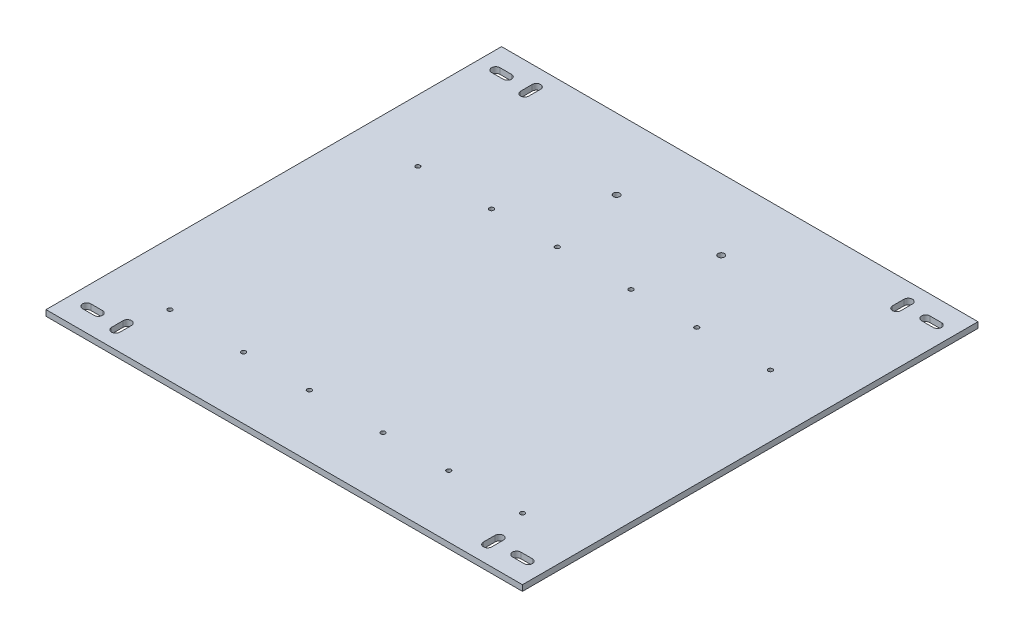
SolidWorks part; units mm, degrees
ref_plane "Front Plane" through (0, 0, 0) normal (0, 0, 1) x (1, 0, 0)
ref_plane "Top Plane" through (0, 0, 0) normal (0, 1, 0) x (1, 0, 0)
ref_plane "Right Plane" through (0, 0, 0) normal (1, 0, 0) x (0, 0, -1)
sketch "Sketch1" plane through (0, 0, 0) normal (0, 1, 0) x (1, 0, 0)
  line L1 (-205, -196) -> (205, -196)
  line L2 (-205, -196) -> (-205, 196)
  line L3 (-205, 196) -> (205, 196)
  line L4 (205, -196) -> (205, 196)
  line L5 (-205, -196) -> (205, 196) construction
  line L6 (-205, 196) -> (205, -196) construction
  point P0 (0, 0)
  dimension "D1" = 410
  dimension "D2" = 392
extrude "Boss-Extrude1" add sketch "Sketch1" along normal blind 5
sketch "Sketch2" plane through (0, 5, 0) normal (0, 1, 0) x (1, 0, 0)
  line L0 (-190, -176) -> (-180, -176) construction
  line L1 (-190, -172.4) -> (-180, -172.4)
  line L2 (-190, -179.6) -> (-180, -179.6)
  line L3 (-205, -196) -> (205, -196) construction
  line L4 (-160, -171) -> (-160, -181) construction
  line L5 (-156.4, -171) -> (-156.4, -181)
  line L6 (-163.6, -171) -> (-163.6, -181)
  line L14 (200, -191) -> (200, 191)
  line L15 (-200, -191) -> (200, -191)
  line L16 (-200, 191) -> (-200, -191)
  line L17 (200, 191) -> (-200, 191)
  line L18 (200, -191) -> (200, 191) construction
  line L19 (-200, -191) -> (200, -191) construction
  line L20 (-200, 191) -> (-200, -191) construction
  line L21 (200, 191) -> (-200, 191) construction
  arc A8 (-190, -172.4) -> (-190, -179.6) centre (-190, -176) ccw
  arc A9 (-180, -179.6) -> (-180, -172.4) centre (-180, -176) ccw
  arc A10 (-156.4, -171) -> (-163.6, -171) centre (-160, -171) ccw
  arc A11 (-163.6, -181) -> (-156.4, -181) centre (-160, -181) ccw
  point P2 (-185, -176)
  point P11 (-160, -176)
  dimension "D2" = 20
  dimension "D5" = 3.6
  dimension "D9" = 3.6
  dimension "D3" = 10
  dimension "D4" = 20
  dimension "D6" = 10
  dimension "D7" = 20
  dimension "D8" = 40
  dimension "D1" = 5
sketch "Sketch3" plane through (0, 5, 0) normal (0, 1, 0) x (1, 0, 0)
  line L0 (-205, 196) -> (-205, -196) construction
  line L1 (-155, 74) -> (-85, 74) construction
  line L2 (-155, 74) -> (-155, -146) construction
  line L3 (-155, -146) -> (-85, -146) construction
  line L4 (-85, 74) -> (-85, -146) construction
  line L5 (-35, 74) -> (35, 74) construction
  line L6 (-35, 74) -> (-35, -146) construction
  line L7 (-35, -146) -> (35, -146) construction
  line L8 (35, 74) -> (35, -146) construction
  line L9 (85, 74) -> (155, 74) construction
  line L10 (85, 74) -> (85, -146) construction
  line L11 (85, -146) -> (155, -146) construction
  line L12 (155, 74) -> (155, -146) construction
  line L13 (-205, -196) -> (205, -196) construction
  line L14 (-48.5, 146) -> (-48.5, 124) construction
  line L15 (-48.5, 124) -> (48.5, 124) construction
  line L16 (48.5, 124) -> (48.5, 146) construction
  line L17 (48.5, 146) -> (-48.5, 146) construction
  line L18 (205, 196) -> (-205, 196) construction
  point P23 (0, 196)
  point P24 (0, 146)
  dimension "D1" = 220
  dimension "D2" = 70
  dimension "D3" = 50
  dimension "D4" = 50
  dimension "D5" = 50
  dimension "D6" = 50
  dimension "D7" = 22
  dimension "D8" = 97
  dimension "D9" = 50
hole_wizard "Hole1" positions "Sketch4" profile "Sketch5" legacy end condition through all
sketch "Sketch4" plane through (0, 5, 0) normal (0, 1, 0) x (1, 0, 0)
  line L0 (-151.7, 70.7) -> (-88.3, 70.7) construction
  line L1 (-88.3, 70.7) -> (-88.3, -142.7) construction
  line L2 (-88.3, -142.7) -> (-151.7, -142.7) construction
  line L3 (-151.7, -142.7) -> (-151.7, 70.7) construction
  line L5 (-155, 74) -> (-85, 74) construction
  line L6 (-155, 74) -> (-155, -146) construction
  line L7 (-31.7, 70.7) -> (31.7, 70.7) construction
  line L8 (31.7, 70.7) -> (31.7, -142.7) construction
  line L9 (31.7, -142.7) -> (-31.7, -142.7) construction
  line L10 (-31.7, -142.7) -> (-31.7, 70.7) construction
  line L13 (-35, 74) -> (-35, -146) construction
  line L14 (88.3, 70.7) -> (151.7, 70.7) construction
  line L15 (151.7, 70.7) -> (151.7, -142.7) construction
  line L16 (151.7, -142.7) -> (88.3, -142.7) construction
  line L17 (88.3, -142.7) -> (88.3, 70.7) construction
  line L19 (85, 74) -> (85, -146) construction
  point P0 (-151.7, 70.7)
  point P2 (-88.3, 70.7)
  point P4 (-151.7, -142.7)
  point P6 (-88.3, -142.7)
  point P8 (-31.7, 70.7)
  point P10 (31.7, 70.7)
  point P12 (-31.7, -142.7)
  point P14 (31.7, -142.7)
  point P16 (88.3, 70.7)
  point P18 (151.7, 70.7)
  point P20 (88.3, -142.7)
  point P22 (151.7, -142.7)
  dimension "D1" = 213.4
  dimension "D2" = 63.4
  dimension "D3" = 3.3
  dimension "D4" = 3.3
  dimension "D5" = 3.3
  dimension "D6" = 3.3
sketch "Sketch5" plane through (-151.7, 5, -70.7) normal (1, 0, 0) x (0, 0, 1)
  line L0 (0, 0) -> (0, 5)
  line L1 (0, 5) -> (1.6, 5)
  line L2 (1.6, 5) -> (1.6, 4)
  line L3 (1.6, 4) -> (1.9, 4)
  line L4 (1.9, 4) -> (1.9, 0)
  line L5 (1.9, 0) -> (0, 0)
  line L6 (0, 110) -> (0, -10) construction
  dimension "Diameter" = 3.2
  dimension "Depth" = 5
  dimension "C-Bore Diameter" = 3.8
  dimension "C-Bore Depth" = 4
extrude "Cut-Extrude2" cut sketch "Sketch2" against normal up to next
mirror "Mirror1" about plane through (0, 0, 0) normal (1, 0, 0) of "Cut-Extrude2" second plane through (0, 0, 0) second plane normal (0, 0, 1)
hole_wizard "Hole2" positions "Sketch6" profile "Sketch7" legacy end condition up to next
sketch "Sketch6" plane through (0, 5, 0) normal (0, 1, 0) x (1, 0, 0)
  line L0 (-45, 135) -> (45, 135) construction
  line L2 (48.5, 146) -> (-48.5, 146) construction
  line L3 (-48.5, 146) -> (-48.5, 124) construction
  point P0 (-45, 135)
  point P2 (45, 135)
  point P11 (0, 146)
  point P12 (0, 135)
  point P16 (-48.5, 135)
  dimension "D1" = 90
sketch "Sketch7" plane through (-45, 5, -135) normal (1, 0, 0) x (0, 0, 1)
  line L0 (0, 0) -> (0, 5)
  line L1 (0, 5) -> (2.4, 5)
  line L2 (2.4, 5) -> (2.4, 4)
  line L3 (2.4, 4) -> (2.7, 4)
  line L4 (2.7, 4) -> (2.7, 0)
  line L5 (2.7, 0) -> (0, 0)
  line L6 (0, 110) -> (0, -10) construction
  dimension "Diameter" = 4.8
  dimension "Depth" = 5
  dimension "C-Bore Diameter" = 5.4
  dimension "C-Bore Depth" = 4
